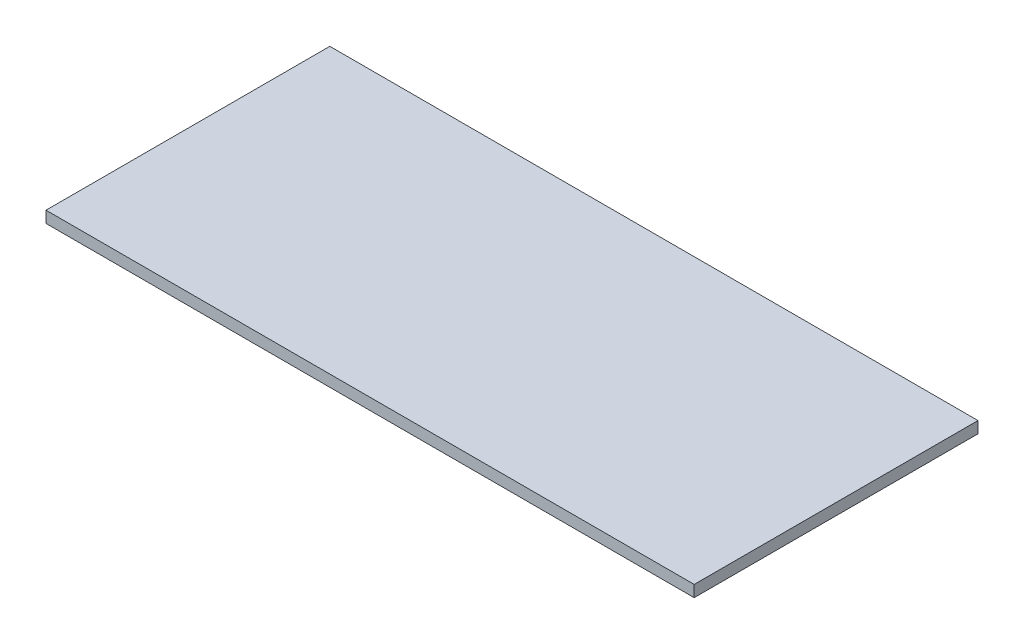
SolidWorks part; units mm, degrees
ref_plane "Спереди" through (0, 0, 0) normal (0, 0, 1) x (1, 0, 0)
ref_plane "Сверху" through (0, 0, 0) normal (0, 1, 0) x (1, 0, 0)
ref_plane "Справа" through (0, 0, 0) normal (1, 0, 0) x (0, 0, -1)
sketch "Эскиз1" plane through (0, 0, 0) normal (0, 1, 0) x (1, 0, 0)
  line L1 (0, 0) -> (84.5, 0)
  line L2 (0, 0) -> (0, -37)
  line L3 (0, -37) -> (84.5, -37)
  line L4 (84.5, 0) -> (84.5, -37)
  dimension "D1" = 37
  dimension "D2" = 84.5
extrude "Бобышка-Вытянуть1" add sketch "Эскиз1" along normal blind 1.5
